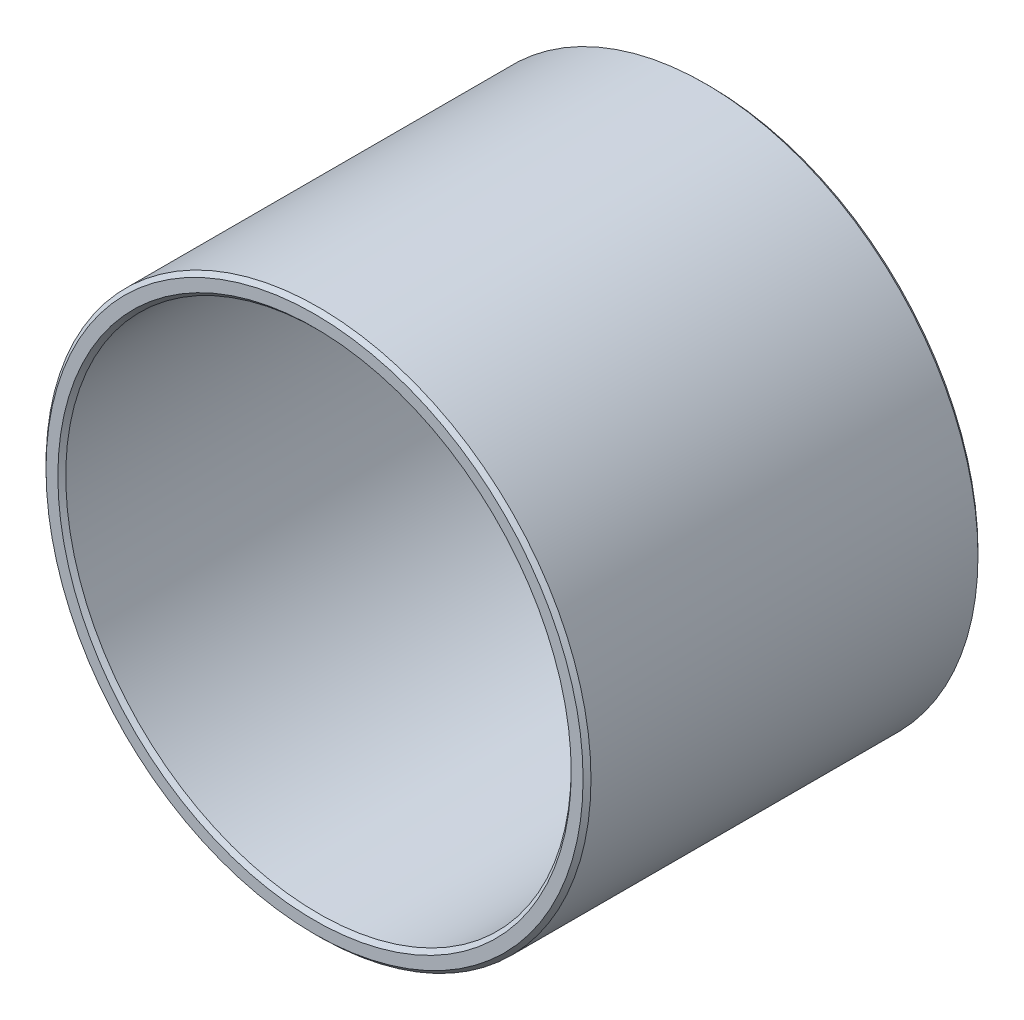
SolidWorks part; units mm, degrees
ref_plane "Front Plane" through (0, 0, 0) normal (0, 0, 1) x (1, 0, 0)
ref_plane "Top Plane" through (0, 0, 0) normal (0, 1, 0) x (1, 0, 0)
ref_plane "Right Plane" through (0, 0, 0) normal (1, 0, 0) x (0, 0, -1)
sketch "Sketch1" plane through (0, 0, 0) normal (0, 0, 1) x (1, 0, 0)
  circle A1 centre (0, 0) radius 32
  circle A2 centre (0, 0) radius 34.5
  circle A3 centre (0, 0) radius 32 construction
  dimension "D1" = 2.5
extrude "Boss-Extrude1" add sketch "Sketch1" against normal up to surface (50 mm away) from surface at 17.5 contours A2 A1
chamfer "Chamfer1" distance 0.5 angle 45 4 edges at (32, 0, -32.5) (32, 0, 17.5) (34.5, 0, -32.5) (34.5, 0, 17.5)
